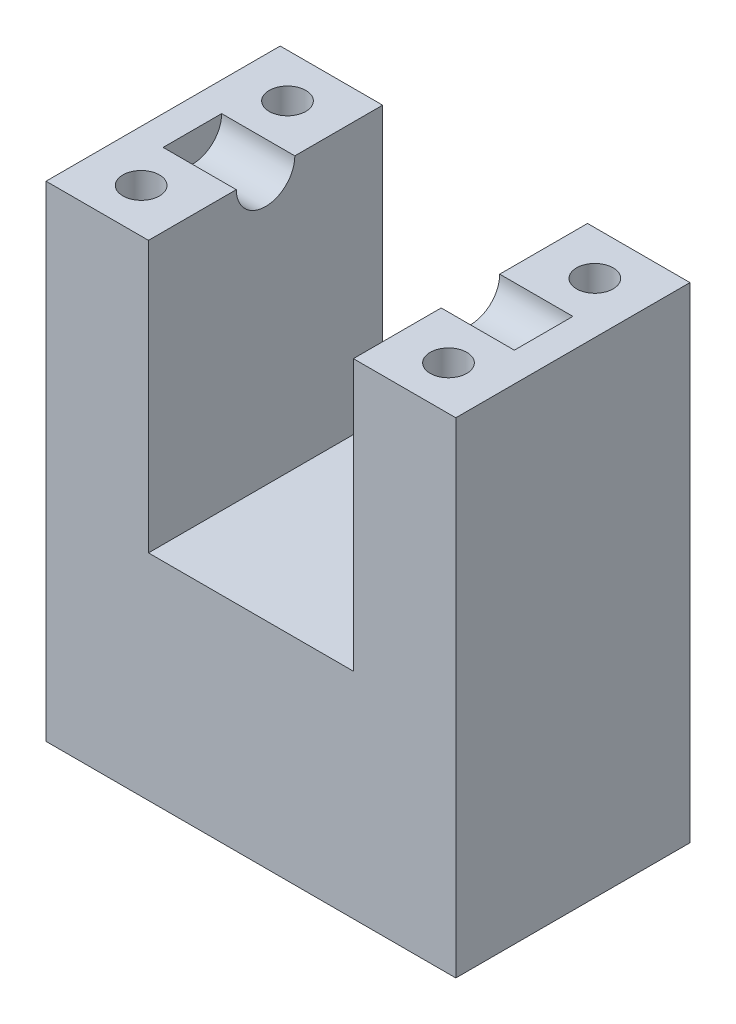
SolidWorks part; units mm, degrees
ref_plane "Front Plane" through (0, 0, 0) normal (0, 0, 1) x (1, 0, 0)
ref_plane "Top Plane" through (0, 0, 0) normal (0, 1, 0) x (1, 0, 0)
ref_plane "Right Plane" through (0, 0, 0) normal (1, 0, 0) x (0, 0, -1)
sketch "Sketch1" plane through (0, 0, 0) normal (0, 1, 0) x (1, 0, 0)
  line L0 (0, 0) -> (44.45, 0)
  line L1 (44.45, 0) -> (44.45, 25.4)
  line L2 (44.45, 25.4) -> (20.066, 25.4)
  line L3 (20.066, 25.4) -> (20.066, 39.116)
  line L4 (20.066, 39.116) -> (0, 39.116)
  line L5 (0, 39.116) -> (0, 0)
  dimension "D1" = 39.116
  dimension "D2" = 44.45
  dimension "D3" = 20.066
  dimension "D4" = 25.4
extrude "L-Base" add sketch "Sketch1" along normal blind 12.7
sketch "Sketch3" plane through (0, 12.7, 0) normal (0, 1, 0) x (1, 0, 0)
  line L1 (0, 0) -> (44.45, 0)
  line L2 (0, 0) -> (0, 25.4)
  line L3 (0, 25.4) -> (44.45, 25.4)
  line L4 (44.45, 0) -> (44.45, 25.4)
  line L5 (0, 0) -> (44.45, 25.4) construction
  line L6 (0, 25.4) -> (44.45, 0) construction
  point P5 (22.225, 12.7)
extrude "Rectangular Extrude" add sketch "Sketch3" along normal offset from surface (10.5664 mm away) 23.2664 up to face at (21.5053, 0, -21.5053)
sketch "Sketch4" plane through (0, 23.2664, 0) normal (0, 1, 0) x (1, 0, 0)
  line L0 (20.066, 25.4) -> (0, 25.4) construction
  line L1 (0, 0) -> (11.1125, 0)
  line L2 (0, 0) -> (0, 25.4)
  line L3 (0, 25.4) -> (11.1125, 25.4)
  line L4 (11.1125, 0) -> (11.1125, 25.4)
  line L5 (0, 0) -> (11.1125, 25.4) construction
  line L6 (0, 25.4) -> (11.1125, 0) construction
  line L7 (44.45, 25.4) -> (0, 25.4) construction
  line L8 (44.45, 0) -> (33.3375, 0)
  line L9 (44.45, 0) -> (44.45, 25.4)
  line L10 (44.45, 25.4) -> (33.3375, 25.4)
  line L11 (33.3375, 0) -> (33.3375, 25.4)
  line L12 (44.45, 0) -> (33.3375, 25.4) construction
  line L13 (44.45, 25.4) -> (33.3375, 0) construction
  line L14 (22.225, 0) -> (22.225, 25.4) construction
  line L15 (0, 0) -> (44.45, 0) construction
  point P4 (5.5563, 12.7)
  point P12 (38.8937, 12.7)
  dimension "D1" = 11.1125
  dimension "D2" = 11.1125
extrude "Fork Extrude" add sketch "Sketch4" along normal blind 29.3624
sketch "Sketch6" plane through (0, 52.6288, 0) normal (0, 1, 0) x (1, 0, 0)
  line L0 (0, 12.7) -> (44.45, 12.7) construction
  line L1 (0, 25.4) -> (0, 0) construction
  line L2 (44.45, 0) -> (44.45, 25.4) construction
  line L4 (3.175, 12.7) -> (41.275, 12.7)
  line L5 (3.175, 12.7) -> (3.175, 9.525)
  line L6 (3.175, 9.525) -> (41.275, 9.525)
  line L7 (41.275, 12.7) -> (41.275, 9.525)
  line L8 (3.175, 12.7) -> (41.275, 9.525) construction
  line L9 (3.175, 9.525) -> (41.275, 12.7) construction
  point P10 (22.225, 11.1125)
  dimension "D1" = 3.175
  dimension "D2" = 38.1
  dimension "D3" = 3.175
revolve "Shaft Recess" cut sketch "Sketch6" angle 360 about L0
hole_wizard "#4 Expansion Insert Recesses #1" positions "Sketch8" profile "Sketch7" counterbore size "#4" standard "ANSI Inch"
sketch "Sketch8" plane through (0, 52.6288, 0) normal (0, 1, 0) x (1, 0, 0)
  line L0 (5.5562, 25.4) -> (5.5562, 0) construction
  line L1 (11.1125, 25.4) -> (0, 25.4) construction
  line L2 (0, 0) -> (11.1125, 0) construction
  line L4 (38.8937, 25.4) -> (38.8937, 0) construction
  line L5 (44.45, 25.4) -> (33.3375, 25.4) construction
  line L6 (33.3375, 0) -> (44.45, 0) construction
  line L8 (11.1125, 20.6375) -> (0, 20.6375) construction
  line L9 (11.1125, 15.875) -> (11.1125, 25.4) construction
  line L10 (0, 25.4) -> (0, 0) construction
  line L12 (11.1125, 4.7625) -> (0, 4.7625) construction
  line L13 (11.1125, 0) -> (11.1125, 9.525) construction
  line L15 (33.3375, 20.6375) -> (44.45, 20.6375) construction
  line L16 (33.3375, 25.4) -> (33.3375, 15.875) construction
  line L17 (44.45, 0) -> (44.45, 25.4) construction
  line L19 (33.3375, 4.7625) -> (44.45, 4.7625) construction
  line L20 (33.3375, 25.4) -> (33.3375, 0) construction
  point P0 (5.5562, 20.6375)
  point P2 (5.5562, 4.7625)
  point P4 (38.8937, 20.6375)
  point P6 (38.8937, 4.7625)
sketch "Sketch7" plane through (5.5562, 52.6288, -20.6375) normal (1, 0, 0) x (0, 0, 1)
  line L0 (0, 0) -> (0, 20.0306)
  line L1 (0, 20.0306) -> (1.6319, 19.05)
  line L2 (1.6319, 19.05) -> (1.6319, 4.7625)
  line L3 (1.6319, 4.7625) -> (1.9844, 4.7625)
  line L4 (1.9844, 4.7625) -> (1.9844, 0)
  line L5 (1.9844, 0) -> (0, 0)
  line L10 (0, 20.0306) -> (-1.632, 19.05) construction
  line L11 (0, -6.35) -> (0, 107.95) construction
  dimension "Hole Dia." = 3.2639
  dimension "Hole Depth" = 19.05
  dimension "C'Bore Dia." = 3.9688
  dimension "C'Bore Depth" = 4.7625
  dimension "Drill Angle" = 118
hole_wizard "#4 Expansion Insert Recesses #2" positions "Sketch11" profile "Sketch10" counterbore size "#4" standard "ANSI Inch"
sketch "Sketch11" plane through (0, 0, 0) normal (0, -1, 0) x (-1, 0, 0)
  line L0 (0, 39.116) -> (0, 0) construction
  line L1 (0, 0) -> (-44.45, 0) construction
  point P0 (-10.033, 10.033)
  point P2 (-29.083, 10.033)
  point P4 (-10.033, 29.083)
  dimension "D1" = 10.033
  dimension "D2" = 10.033
  dimension "D3" = 19.05
  dimension "D4" = 19.05
sketch "Sketch10" plane through (10.033, 0, -10.033) normal (1, 0, 0) x (0, 0, -1)
  line L0 (0, 0) -> (0, 10.5056)
  line L1 (0, 10.5056) -> (1.6319, 9.525)
  line L2 (1.6319, 9.525) -> (1.6319, 4.7625)
  line L3 (1.6319, 4.7625) -> (1.9844, 4.7625)
  line L4 (1.9844, 4.7625) -> (1.9844, 0)
  line L5 (1.9844, 0) -> (0, 0)
  line L10 (0, 10.5056) -> (-1.632, 9.525) construction
  line L11 (0, -6.35) -> (0, 107.95) construction
  dimension "Hole Dia." = 3.2639
  dimension "Hole Depth" = 9.525
  dimension "C'Bore Dia." = 3.9688
  dimension "C'Bore Depth" = 4.7625
  dimension "Drill Angle" = 118
